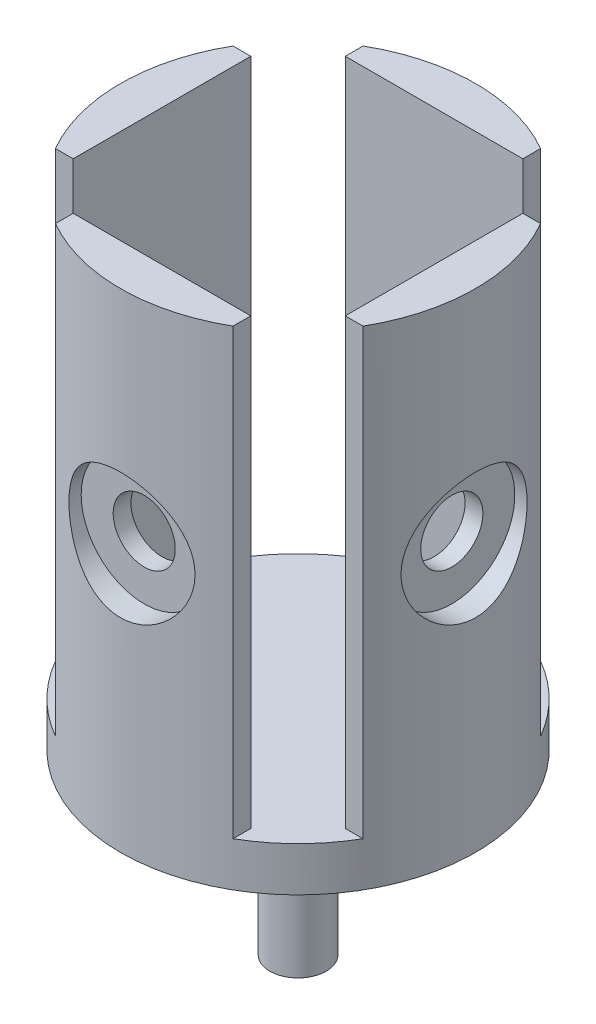
SolidWorks part; units mm, degrees
ref_plane "Front Plane" through (0, 0, 0) normal (0, 0, 1) x (1, 0, 0)
ref_plane "Top Plane" through (0, 0, 0) normal (0, 1, 0) x (1, 0, 0)
ref_plane "Right Plane" through (0, 0, 0) normal (1, 0, 0) x (0, 0, -1)
sketch "Sketch1" plane through (0, 0, 0) normal (0, 1, 0) x (1, 0, 0)
  circle A0 centre (0, 0) radius 10
extrude "Boss-Extrude1" add sketch "Sketch1" along normal blind 2.5
sketch "Sketch3" plane through (0, 2.5, 0) normal (0, 1, 0) x (1, 0, 0)
  line L0 (0, -1.375) -> (0, 1.375) construction
  line L1 (-5, 8.6603) -> (-5, 7.6603)
  line L2 (5, 8.6603) -> (5, 7.6603)
  line L3 (5, 7.6603) -> (-5, 7.6603)
  line L4 (-1.375, 0) -> (1.375, 0) construction
  line L5 (5, -8.6603) -> (5, -7.6603)
  line L6 (-5, -8.6603) -> (-5, -7.6603)
  line L7 (5, -7.6603) -> (-5, -7.6603)
  line L8 (-8.6603, -5) -> (-7.6603, -5)
  line L9 (-7.6603, -5) -> (-7.6603, 5)
  line L10 (-8.6603, 5) -> (-7.6603, 5)
  line L11 (-5, 8.6603) -> (-5, 7.6603)
  line L12 (-5, 7.6603) -> (5, 7.6603)
  line L13 (5, 8.6603) -> (5, 7.6603)
  line L14 (8.6603, 5) -> (7.6603, 5)
  line L15 (7.6603, 5) -> (7.6603, -5)
  line L16 (8.6603, -5) -> (7.6603, -5)
  arc A0 (5, 8.6603) -> (-5, 8.6603) centre (0, 0) ccw
  arc A2 (5, -8.6603) -> (-5, -8.6603) centre (0, 0) cw
  arc A3 (-8.6603, -5) -> (-8.6603, 5) centre (0, 0) cw
  arc A4 (-5, 8.6603) -> (5, 8.6603) centre (0, 0) cw
  arc A5 (8.6603, 5) -> (8.6603, -5) centre (0, 0) cw
  circle M9 centre (0, 0) radius 10
  dimension "D1" = 4
extrude "Boss-Extrude2" add sketch "Sketch3" along normal blind 25 contours L10 L8 L9 M9 | L5 L7 L6 M9 | L16 L14 L15 M9 | L3 L2 L1 M9
sketch "Sketch5" plane through (0, 0, 0) normal (0, -1, 0) x (-1, 0, 0)
  circle A0 centre (0, 0) radius 1.587
extrude "Boss-Extrude3" add sketch "Sketch5" along normal blind 10
sketch "Sketch6" plane through (0, 0, 7.6603) normal (0, 0, -1) x (-1, 0, 0)
  line L0 (0, 0) -> (0, 15) construction
ref_plane "Plane1" through (0, 15, 0) normal (0, 1, 0) x (1, 0, 0)
sketch "Sketch7" plane through (0, 15, 0) normal (0, 1, 0) x (1, 0, 0)
  line L0 (0, 0) -> (0, 7.6603) construction
  line L1 (5, 7.6603) -> (-5, 7.6603) construction
  line L2 (0, 7.6603) -> (1.75, 7.6603)
  line L3 (5, 7.6603) -> (-5, 7.6603) construction
  line L4 (1.75, 7.6603) -> (1.75, 8.6603)
  line L5 (1.75, 8.6603) -> (3.55, 8.6603)
  line L6 (3.55, 8.6603) -> (3.55, 10.3184)
  line L7 (3.55, 10.3184) -> (0, 10.3184)
  line L8 (0, 10.3184) -> (0, 7.6603)
revolve "Cut-Revolve1" cut sketch "Sketch7" angle 360 about L0
pattern_circular "CirPattern2" count 4 every 90 about axis through (0, 0, 0) along (0, 1, 0) of "Cut-Revolve1"
